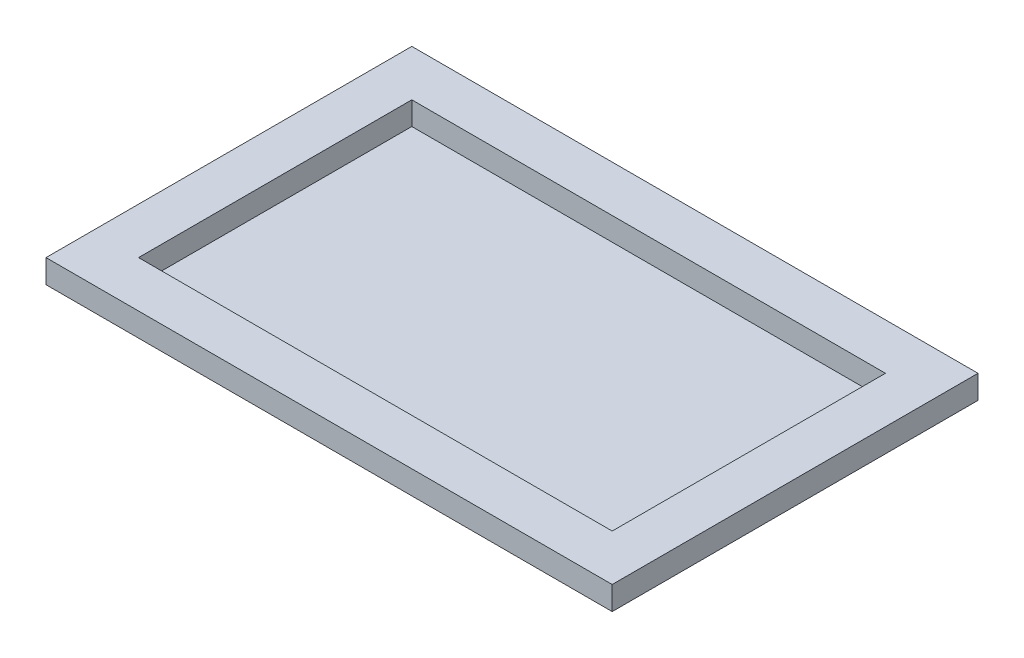
SolidWorks part; units mm, degrees
ref_plane "Alzado" through (0, 0, 0) normal (0, 0, 1) x (1, 0, 0)
ref_plane "Planta" through (0, 0, 0) normal (0, 1, 0) x (1, 0, 0)
ref_plane "Vista lateral" through (0, 0, 0) normal (1, 0, 0) x (0, 0, -1)
sketch "Croquis1" plane through (0, 0, 0) normal (0, 1, 0) x (1, 0, 0)
  line L1 (130, -75) -> (-130, -75)
  line L2 (130, -75) -> (130, 75)
  line L3 (130, 75) -> (-130, 75)
  line L4 (-130, -75) -> (-130, 75)
  line L5 (130, -75) -> (-130, 75) construction
  line L6 (130, 75) -> (-130, -75) construction
  line L7 (155.4, -100.4) -> (-155.4, -100.4)
  line L8 (155.4, -100.4) -> (155.4, 100.4)
  line L9 (155.4, 100.4) -> (-155.4, 100.4)
  line L10 (-155.4, -100.4) -> (-155.4, 100.4)
  line L11 (155.4, -100.4) -> (-155.4, 100.4) construction
  line L12 (155.4, 100.4) -> (-155.4, -100.4) construction
  point P0 (0, 0)
  point P6 (0, 0)
  dimension "D1" = 260
  dimension "D2" = 150
  dimension "D3" = 25.4
  dimension "D4" = 25.4
extrude "Saliente-Extruir1" add sketch "Croquis1" along normal blind 12.7
sketch "Croquis2" plane through (0, 0, 0) normal (0, -1, 0) x (1, 0, 0)
  line L0 (-155.4, -100.4) -> (-155.4, 100.4) construction
  line L1 (155.4, -100.4) -> (-155.4, -100.4) construction
  line L2 (155.4, 100.4) -> (155.4, -100.4) construction
  line L3 (-155.4, 100.4) -> (155.4, 100.4) construction
  line L4 (-155.4, -100.4) -> (-155.4, 100.4)
  line L5 (155.4, -100.4) -> (-155.4, -100.4)
  line L6 (155.4, 100.4) -> (155.4, -100.4)
  line L7 (-155.4, 100.4) -> (155.4, 100.4)
extrude "Saliente-Extruir2" add sketch "Croquis2" along normal blind 0.2
